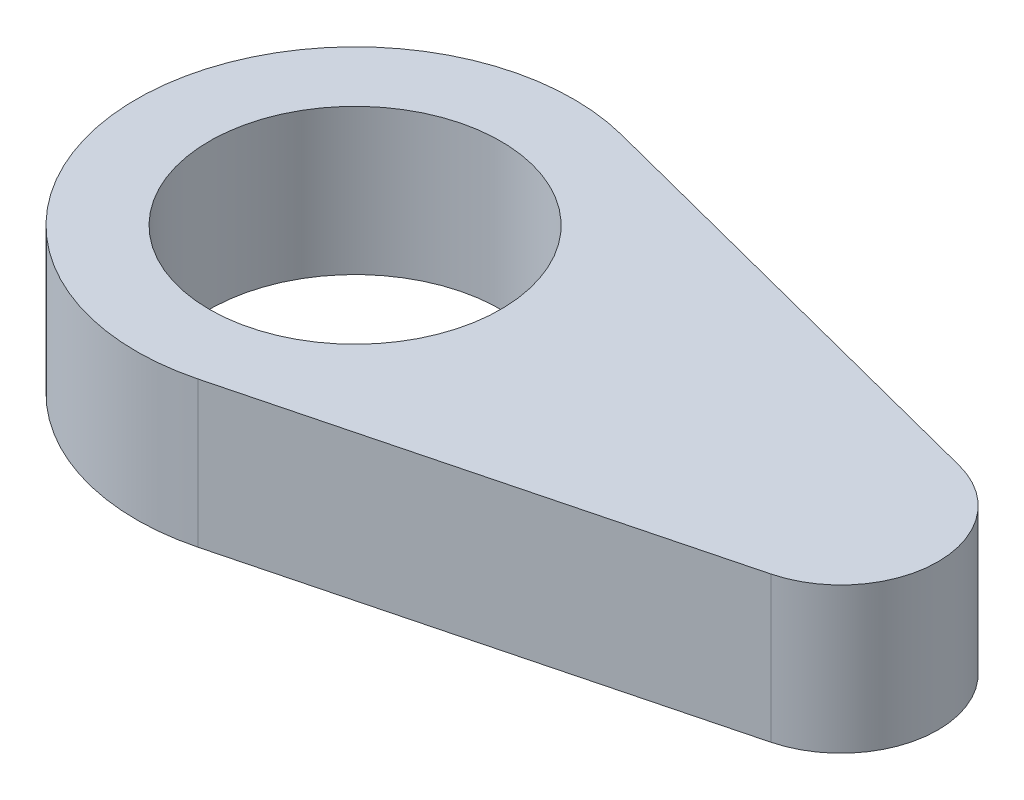
SolidWorks part; units mm, degrees
ref_plane "前视基准面" through (0, 0, 0) normal (0, 0, 1) x (1, 0, 0)
ref_plane "上视基准面" through (0, 0, 0) normal (0, 1, 0) x (1, 0, 0)
ref_plane "右视基准面" through (0, 0, 0) normal (1, 0, 0) x (0, 0, -1)
other "Configuration Table"
sketch "草图1" plane through (0, 0, 0) normal (0, 1, 0) x (1, 0, 0)
  line L1 (10.5, 1.9365) -> (1.125, 4.3571)
  line L2 (10.5, -1.9365) -> (1.125, -4.3571)
  circle A0 centre (0, 0) radius 3
  circle A1 centre (0, 0) radius 4.5
  circle A2 centre (10, 0) radius 2
  dimension "D1" = 9
  dimension "D2" = 6
  dimension "D3" = 4
  dimension "D4" = 10
extrude "凸台-拉伸1" add sketch "草图1" along normal blind 3 contours A1 A0 | A2 L1 A1 L2 | A2 A0
